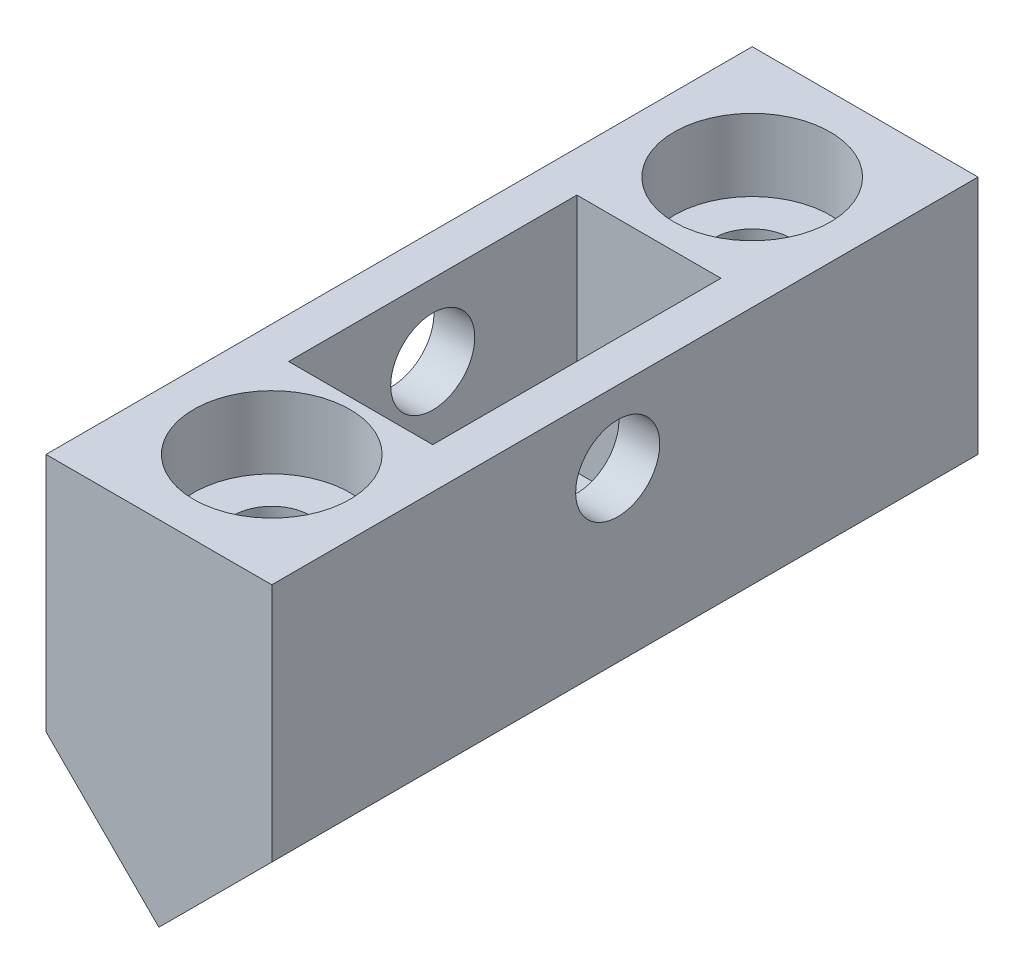
SolidWorks part; units mm, degrees
ref_plane "Front Plane" through (0, 0, 0) normal (0, 0, 1) x (1, 0, 0)
ref_plane "Top Plane" through (0, 0, 0) normal (0, 1, 0) x (1, 0, 0)
ref_plane "Right Plane" through (0, 0, 0) normal (1, 0, 0) x (0, 0, -1)
sketch "Sketch1" plane through (0, 0, 0) normal (0, 0, 1) x (1, 0, 0)
  line L0 (0, 5) -> (0, -56.5295) construction
  line L1 (-4.7, 5) -> (4.7, 5)
  line L2 (-4.7, 5) -> (-4.7, -5)
  line L4 (4.7, 5) -> (4.7, -5)
  line L5 (-4.7, 5) -> (4.7, -5) construction
  line L6 (-4.7, -5) -> (4.7, 5) construction
  line L7 (-4.7, -5) -> (0, -9.7)
  line L8 (0, -9.7) -> (4.7, -5)
  point P0 (0, 0)
  dimension "D1" = 90
  dimension "D2" = 9.4
  dimension "D3" = 10
extrude "Boss-Extrude1" add sketch "Sketch1" along normal blind 14.4 and the other way blind 15
sketch "Sketch2" plane through (0, 5, 0) normal (0, 1, 0) x (1, 0, 0)
  line L1 (-3, 6) -> (3, 6)
  line L2 (-3, 6) -> (-3, -6)
  line L3 (-3, -6) -> (3, -6)
  line L4 (3, 6) -> (3, -6)
  line L5 (-3, 6) -> (3, -6) construction
  line L6 (-3, -6) -> (3, 6) construction
  point P0 (0, 0)
  dimension "D1" = 6
  dimension "D2" = 12
extrude "Cut-Extrude1" cut sketch "Sketch2" against normal blind 10
sketch "Sketch3" plane through (4.7, 0, 0) normal (1, 0, 0) x (0, 0, -1)
  line L0 (0, 0) -> (0, 5) construction
  line L2 (15, 5) -> (-14.4, 5) construction
  circle A0 centre (0, 2) radius 1.75
  point P3 (0, 5)
  point P7 (0, 0)
  dimension "D1" = 3.5
  dimension "D2" = 3
extrude "Cut-Extrude2" cut sketch "Sketch3" against normal through all
hole_wizard "CBORE for M3 SHCS1" positions "Sketch4" profile "Sketch5" counterbore size "M3" standard "ANSI Metric" end condition through all
sketch "Sketch4" plane through (0, 5, 0) normal (0, 1, 0) x (1, 0, 0)
  line L0 (4.7, 0.3) -> (-4.7, 0.3) construction
  line L1 (4.7, 15) -> (4.7, -14.4) construction
  line L2 (-4.7, 15) -> (-4.7, -14.4) construction
  line L4 (0, -14.4) -> (0, 15) construction
  line L5 (4.7, -14.4) -> (-4.7, -14.4) construction
  line L6 (4.7, 15) -> (-4.7, 15) construction
  point P0 (0, -9.7)
  point P20 (0, 10.3)
  dimension "D1" = 20
sketch "Sketch5" plane through (0, 5, 9.7) normal (1, 0, 0) x (0, 0, 1)
  line L0 (0, 0) -> (0, 14.7)
  line L1 (0, 14.7) -> (1.6, 14.7)
  line L3 (1.6, 14.7) -> (1.6, 3)
  line L4 (1.6, 3) -> (3.25, 3)
  line L5 (3.25, 3) -> (3.25, 0)
  line L7 (3.25, 0) -> (0, 0)
  line L11 (0, -6.35) -> (0, 107.95) construction
  dimension "Thru Hole Dia." = 3.2
  dimension "Thru Hole Depth" = 14.7
  dimension "C'Bore Dia." = 6.5
  dimension "C'Bore Depth" = 3
